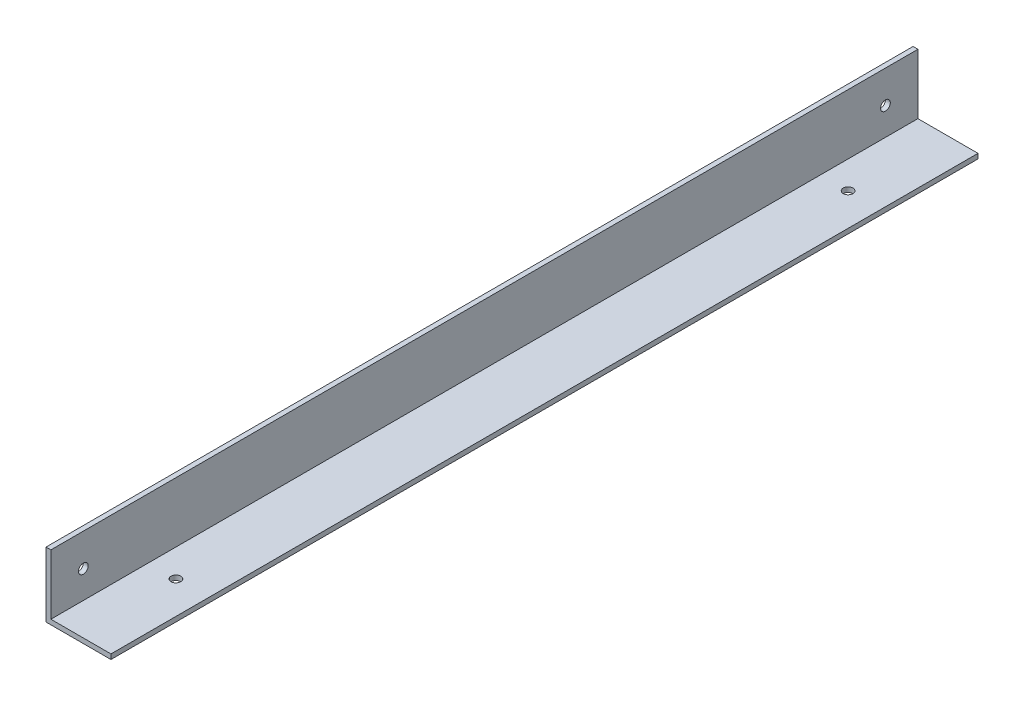
SolidWorks part; units mm, degrees
ref_plane "Plan de face" through (0, 0, 0) normal (0, 0, 1) x (1, 0, 0)
ref_plane "Plan de dessus" through (0, 0, 0) normal (0, 1, 0) x (1, 0, 0)
ref_plane "Plan de droite" through (0, 0, 0) normal (1, 0, 0) x (0, 0, -1)
sketch "Esquisse1" plane through (0, 0, 0) normal (0, 0, 1) x (1, 0, 0)
  line L0 (0, 0) -> (20, 0)
  line L1 (20, 0) -> (20, 1.5)
  line L2 (20, 1.5) -> (1.5, 1.5)
  line L3 (1.5, 1.5) -> (1.5, 20)
  line L4 (1.5, 20) -> (0, 20)
  line L5 (0, 20) -> (0, 0)
  dimension "D1" = 1.5
  dimension "D2" = 1.5
  dimension "D3" = 20
  dimension "D4" = 20
extrude "Extrusion1" add sketch "Esquisse1" along normal blind 267
sketch "Esquisse2" plane through (0, 1.5, 0) normal (0, 1, 0) x (1, 0, 0)
  line L0 (20, -267) -> (20, 0) construction
  line L1 (20, 0) -> (1.5, 0) construction
  line L2 (20, -267) -> (1.5, -267) construction
  circle A0 centre (10, -30) radius 1.5
  circle A1 centre (10, -237) radius 1.5
  point P8 (10.75, -267)
  dimension "D1" = 10
  dimension "D2" = 30
  dimension "D5" = 30
  dimension "D6" = 10
extrude "Extrusion2" cut sketch "Esquisse2" against normal through all
sketch "Esquisse3" plane through (1.5, 0, 0) normal (1, 0, 0) x (0, 0, -1)
  line L0 (-257, 10) -> (-10, 10) construction
  line L1 (-267, 20) -> (0, 20) construction
  line L2 (-267, 1.5) -> (-267, 20) construction
  line L3 (0, 1.5) -> (0, 20) construction
  circle A0 centre (-257, 10) radius 1.5
  circle A1 centre (-10, 10) radius 1.5
  dimension "D2" = 10
  dimension "D1" = 10
  dimension "D3" = 10
extrude "Extrusion3" cut sketch "Esquisse3" against normal blind 264
